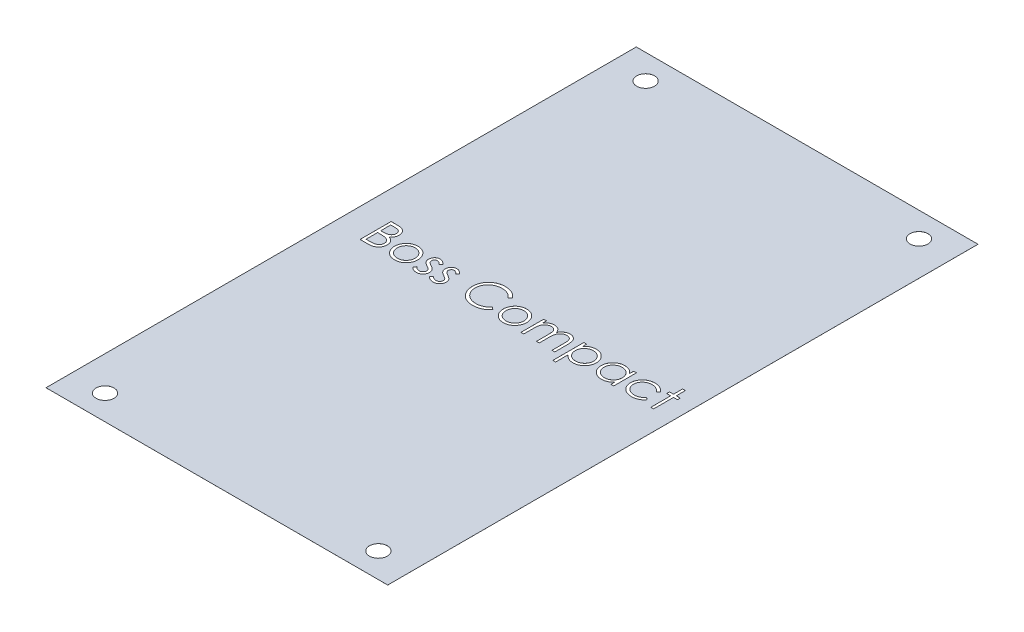
SolidWorks part; units mm, degrees
ref_plane "Front Plane" through (0, 0, 0) normal (0, 0, 1) x (1, 0, 0)
ref_plane "Top Plane" through (0, 0, 0) normal (0, 1, 0) x (1, 0, 0)
ref_plane "Right Plane" through (0, 0, 0) normal (1, 0, 0) x (0, 0, -1)
sketch "Sketch2" plane through (0, 0, 0) normal (0, 1, 0) x (1, 0, 0)
  line L1 (-34.925, -60.325) -> (34.925, -60.325)
  line L2 (-34.925, -60.325) -> (-34.925, 60.325)
  line L3 (-34.925, 60.325) -> (34.925, 60.325)
  line L4 (34.925, -60.325) -> (34.925, 60.325)
  line L5 (-34.925, -60.325) -> (34.925, 60.325) construction
  line L6 (-34.925, 60.325) -> (34.925, -60.325) construction
  point P0 (0, 0)
  dimension "D1" = 120.65
  dimension "D2" = 69.85
extrude "Boss-Extrude1" add sketch "Sketch2" along normal blind 0.0025
sketch "Sketch3" plane through (0, 0.0025, 0) normal (0, 1, 0) x (1, 0, 0)
  line L1 (-27.94, -55.245) -> (27.94, -55.245)
  line L2 (-27.94, -55.245) -> (-27.94, 55.245)
  line L3 (-27.94, 55.245) -> (27.94, 55.245)
  line L4 (27.94, -55.245) -> (27.94, 55.245)
  line L5 (-27.94, -55.245) -> (27.94, 55.245) construction
  line L6 (-27.94, 55.245) -> (27.94, -55.245) construction
  circle A0 centre (-27.94, 55.245) radius 1.8288
  circle A7 centre (27.94, 55.245) radius 1.8288
  circle A8 centre (27.94, -55.245) radius 1.8288
  circle A9 centre (-27.94, -55.245) radius 1.8288
  point P0 (0, 0)
  dimension "D3" = 3.6576
  dimension "D1" = 110.49
  dimension "D2" = 55.88
  dimension "D4" = 2
  dimension "D5" = 2
extrude "Cut-Extrude1" cut sketch "Sketch3" against normal through all contours A9 | A8 | A7 | A0
sketch "Sketch5" plane through (0, 0.0025, 0) normal (0, 1, 0) x (1, 0, 0)
  text T0 "Boss Compact\r\n" font "Century Gothic" height 6.35
extrude "Cut-Extrude2" cut sketch "Sketch5" against normal blind 2.54
